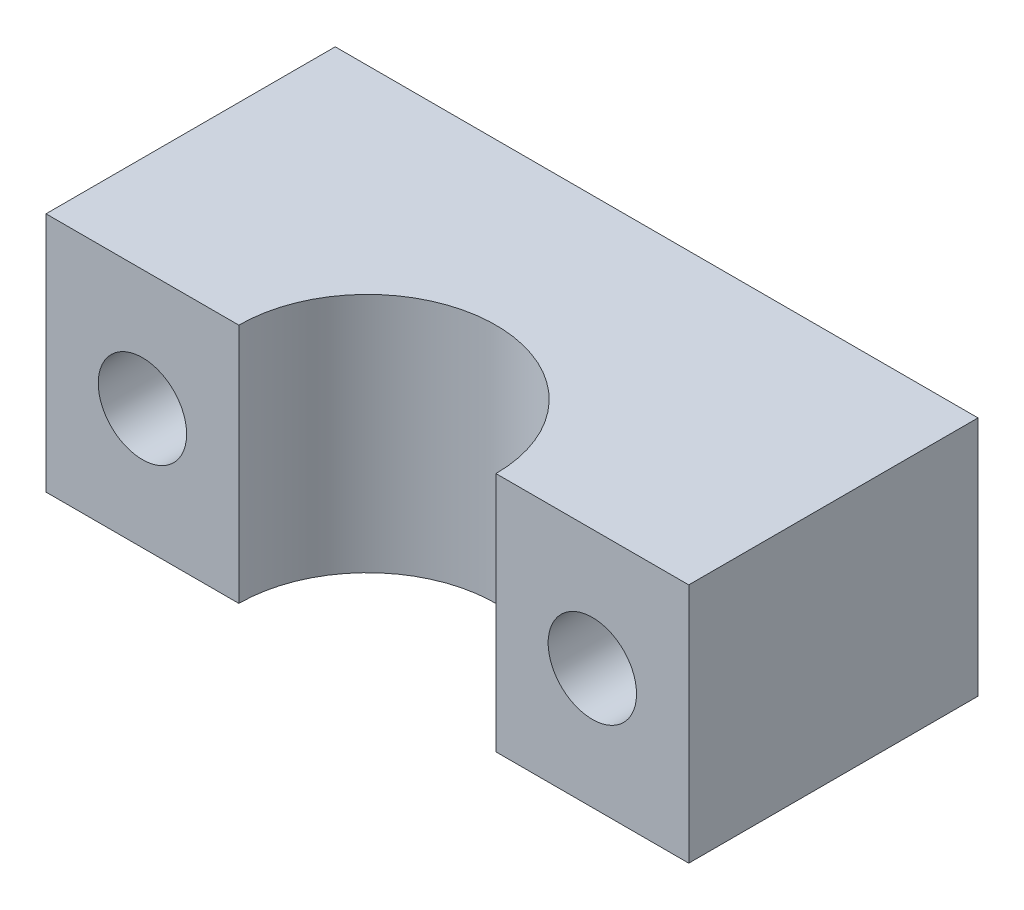
SolidWorks part; units mm, degrees
ref_plane "前视基准面" through (0, 0, 0) normal (0, 0, 1) x (1, 0, 0)
ref_plane "上视基准面" through (0, 0, 0) normal (0, 1, 0) x (1, 0, 0)
ref_plane "右视基准面" through (0, 0, 0) normal (1, 0, 0) x (0, 0, -1)
sketch "草图1" plane through (0, 0, 0) normal (0, 0, 1) x (1, 0, 0)
  line L1 (0, 0) -> (40, 0)
  line L2 (0, 0) -> (0, -15)
  line L3 (0, -15) -> (40, -15)
  line L4 (40, 0) -> (40, -15)
  dimension "D1" = 15
  dimension "D2" = 40
extrude "凸台-拉伸1" add sketch "草图1" along normal blind 18
sketch "草图2" plane through (0, 0, 0) normal (0, 1, 0) x (1, 0, 0)
  line L0 (40, -18) -> (0, -18) construction
  circle A0 centre (20, -18) radius 8
  dimension "D1" = 16
extrude "切除-拉伸1" cut sketch "草图2" against normal blind 15
sketch "草图4" plane through (0, 0, 18) normal (0, 0, 1) x (1, 0, 0)
  line L0 (12, 0) -> (0, 0) construction
  line L1 (40, 0) -> (28, 0) construction
  line L3 (28, 0) -> (12, 0) construction
  circle A0 centre (34, -7.5) radius 2.75
  circle A1 centre (6, -7.5) radius 2.75
  point P4 (22.8995, -7.4144)
  point P13 (20, 0)
  dimension "D1" = 5.5
  dimension "D2" = 5.5
  dimension "D3" = 28
  dimension "D4" = 7.5
  dimension "D5" = 7.5
  dimension "D6" = 14
extrude "切除-拉伸2" cut sketch "草图4" against normal through all
